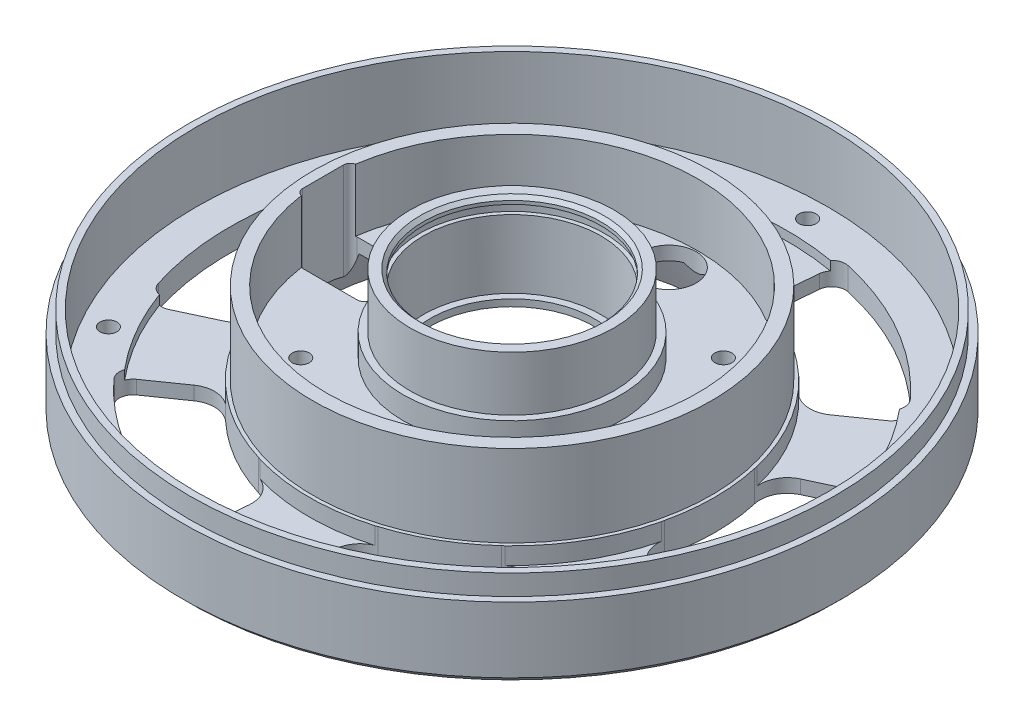
SolidWorks part; units mm, degrees
material "5052-H32"
ref_plane "Front Plane" through (0, 0, 0) normal (0, 0, 1) x (1, 0, 0)
ref_plane "Top Plane" through (0, 0, 0) normal (0, 1, 0) x (1, 0, 0)
ref_plane "Right Plane" through (0, 0, 0) normal (1, 0, 0) x (0, 0, -1)
ref_axis "Axis1" through (0, 0, 0) along (0, 1, 0)
sketch "Sketch1" plane through (0, 0, 0) normal (0, 0, 1) x (1, 0, 0)
  line L0 (0, 0) -> (0, -50000) construction
  line L1 (-13.02, 8.15) -> (-13.02, -4.15)
  line L2 (-13.02, -4.15) -> (-12.02, -4.15)
  line L4 (45.1, 8.15) -> (-45.1, 8.15) construction
  line L5 (-12.75, -4.15) -> (12.75, -4.15) construction
  line L7 (-13.02, 8.15) -> (-14.98, 8.15)
  line L8 (-14.98, 8.15) -> (-14.98, -3.15)
  line L9 (-14.98, -3.15) -> (-28.25, -3.15)
  line L10 (-12.02, -5.15) -> (-28.25, -5.15)
  line L12 (-28.25, -5.15) -> (-28.25, -3.15)
  line L13 (-29.25, 6) -> (-29.25, -6) construction
  line L16 (-12.02, -4.15) -> (-12.02, -5.15)
  dimension "D1" = 1
  dimension "D2" = 29.96
  dimension "D3" = 2
  dimension "D4" = 1
  dimension "D5" = 1
  dimension "D6" = 26.04
revolve "Revolve1" add sketch "Sketch1" angle 360 about L0
sketch "Sketch4" plane through (0, 0, 0) normal (0, 0, 1) x (1, 0, 0)
  line L1 (-29.75, -8.5) -> (-40.35, -8.5)
  line L2 (-46.35, -7.15) -> (-46.35, 3)
  line L3 (-46.35, 3) -> (-47.35, 3)
  line L4 (-47.35, 3) -> (-47.35, 0)
  line L5 (-47.35, 0) -> (-48.35, 0)
  line L6 (-48.35, 0) -> (-48.35, -9.6235)
  line L7 (-47.4735, -10.5) -> (-28.75, -10.5)
  line L8 (-28.75, -10.5) -> (-26.75, -5.15)
  line L9 (-29.75, -8.5) -> (-29.75, -6)
  line L10 (-26.75, -5.15) -> (-26.75, -3.15)
  line L12 (-48.35, -9.6235) -> (-47.4735, -10.5)
  line L13 (-45.1, 8.15) -> (-45.1, -6.15) construction
  line L14 (-46.35, -7.15) -> (-40.35, -7.15)
  line L15 (-40.35, -7.15) -> (-40.35, -8.5)
  line L16 (-45.1, -6.15) -> (45.1, -6.15) construction
  line L18 (-44.85, -7.15) -> (-44.85, -10.5) construction
  line L20 (-41.85, -7.15) -> (-41.85, -10.5) construction
  line L21 (-30.25, -6) -> (30.25, -6) construction
  line L22 (-29.75, -6) -> (-29.23, -6)
  line L23 (-29.25, -6) -> (29.25, -6) construction
  line L24 (-29.23, -6) -> (-29.23, -3.15)
  line L25 (-29.23, -3.15) -> (-26.75, -3.15)
  line L26 (28.25, -3.15) -> (-28.25, -3.15) construction
  line L27 (-39.5, -7.5) -> (39.5, -7.5) construction
  line L28 (0, 0) -> (0, 50000) construction
  line L29 (-30.25, -6) -> (-30.25, -7.5) construction
  line L33 (-28.25, -5.15) -> (28.25, -5.15) construction
  dimension "D1" = 2
  dimension "D2" = 3
  dimension "D3" = 1
  dimension "D4" = 2
  dimension "D5" = 0.5
  dimension "D6" = 1
  dimension "D7" = 1.25
  dimension "D8" = 135
  dimension "D9" = 3
  dimension "D10" = 1.5
  dimension "D11" = 1.5
  dimension "D12" = 2
  dimension "D13" = 1
  dimension "D14" = 58.46
revolve "Revolve2" add sketch "Sketch4" angle 360 about axis through (0, 0, 0) along (0, 1, 0)
sketch "Sketch6" plane through (0, 0, 0) normal (0, 0, 1) x (1, 0, 0)
  line L0 (-29.23, 6) -> (-27.23, 6)
  line L1 (-27.23, 6) -> (-27.23, -3.15)
  line L2 (-27.23, -3.15) -> (-29.23, -3.15)
  line L3 (-29.23, -3.15) -> (-29.23, 6)
  line L4 (29.25, 6) -> (-29.25, 6) construction
  line L6 (29.23, -3.15) -> (-29.23, -3.15) construction
  dimension "D1" = 2
revolve "Revolve3" add sketch "Sketch6" angle 360 about axis through (0, 0, 0) along (0, 1, 0)
sketch "Sketch7" plane through (0, 0, 0) normal (0, 0, 1) x (1, 0, 0)
  line L0 (40.35, -8.5) -> (-40.35, -8.5) construction
  line L1 (-29.58, -6) -> (-29.23, -6)
  line L2 (-29.73, -6.15) -> (-29.73, -8.5)
  line L3 (-29.73, -8.5) -> (-29.23, -8.5)
  line L4 (-29.23, -6) -> (-29.23, -8.5)
  line L5 (-29.23, 6) -> (-29.23, -6) construction
  line L6 (-29.58, -6) -> (-29.73, -6.15)
  line L7 (29.75, -8.5) -> (-29.75, -8.5) construction
  line L8 (-31.759, -6.15) -> (-25.7399, -6.15) construction
  line L13 (-30.25, -6) -> (30.25, -6) construction
  dimension "D1" = 135
  dimension "D2" = 0.5
revolve "Revolve4" add sketch "Sketch7" angle 360 about axis through (0, 0, 0) along (0, 1, 0)
sketch "Sketch8" plane through (0, -5.15, 0) normal (0, -1, 0) x (1, 0, 0)
  circle A0 centre (-15.5, 15.5) radius 3.5
  circle A1 centre (15.5, 15.5) radius 3.5
  circle A2 centre (15.5, -15.5) radius 3.5
  circle A3 centre (-15.5, -15.5) radius 3.5
  dimension "D1" = 7
sketch "Sketch10" plane through (0, 0, 0) normal (0, 0, 1) x (1, 0, 0)
  line L0 (-15.25, 0.15) -> (15.25, 0.15) construction
  line L1 (-14.98, -3.15) -> (-15.98, -3.15)
  line L2 (-14.98, -3.15) -> (-14.98, 0.15)
  line L3 (-14.98, 0.15) -> (-15.98, 0.15)
  line L4 (-15.98, -3.15) -> (-15.98, 0.15)
  line L5 (-14.98, 8.15) -> (-14.98, -3.15) construction
  line L6 (14.98, -3.15) -> (-14.98, -3.15) construction
  dimension "D1" = 1
revolve "Revolve5" add sketch "Sketch10" angle 360 about axis through (0, 0, 0) along (0, 1, 0)
sketch "Sketch12" plane through (0, 0, 0) normal (0, 1, 0) x (1, 0, 0)
  circle A0 centre (-23, 0) radius 4
  dimension "D1" = 8
  dimension "D2" = 23
extrude "Cut-Extrude2" cut sketch "Sketch12" against normal through all
pattern_circular "CirPattern3" count 4 over 360 about axis through (0, 0, 0) along (0, 1, 0) of "Cut-Extrude2"
extrude "Boss-Extrude1" add sketch "Sketch8" along normal up to surface (3.85 mm away)
hole_wizard "M3x0.5 Tapped Hole1" positions "Sketch14" profile "Sketch15" tap size "M3x0.5" standard "ANSI Metric" end condition through all
sketch "Sketch14" plane through (0, -9, 0) normal (0, -1, 0) x (-1, 0, 0)
  point P0 (-15.5, 15.5)
  point P3 (15.5, 15.5)
  point P6 (15.5, -15.5)
  point P9 (-15.5, -15.5)
cosmetic thread "Hole Thread1" parameters "D2"=3
cosmetic thread "Hole Thread2" parameters "D2"=3
cosmetic thread "Hole Thread3" parameters "D2"=3
cosmetic thread "Hole Thread4" parameters "D2"=3
sketch "Sketch15" plane through (15.5, -9, -15.5) normal (1, 0, 0) x (0, 0, -1)
  line L0 (0, 0) -> (0, 17.15)
  line L1 (0, 17.15) -> (1.25, 17.15)
  line L2 (1.25, 17.15) -> (1.25, 0)
  line L5 (1.25, 0) -> (0, 0)
  line L11 (0, -6.35) -> (0, 107.95) construction
  dimension "Thru Tap Drill Dia." = 2.5
  dimension "Thru Tap Drill Depth" = 17.15
hole_wizard "M3x0.5 Tapped Hole3" positions "Sketch19" profile "Sketch20" tap size "M3x0.5" standard "ANSI Metric" end condition through all
sketch "Sketch19" plane through (0, -10.5, 0) normal (0, -1, 0) x (-1, 0, 0)
  line L0 (0, 0) -> (0, 43.35) construction
  line L3 (0, 0) -> (-50000, 0) construction
  circle A1 centre (0, 0) radius 43.35 construction
  circle A2 centre (0, 0) radius 40.35 construction
  point P0 (0, 43.35)
  dimension "D1" = 3
  dimension "D2" = 90
sketch "Sketch20" plane through (0, -10.5, -43.35) normal (1, 0, 0) x (0, 0, -1)
  line L0 (0, 0) -> (0, 18.65)
  line L1 (0, 18.65) -> (1.25, 18.65)
  line L2 (1.25, 18.65) -> (1.25, 0.5)
  line L3 (1.25, 0.5) -> (1.75, 0)
  line L5 (1.75, 0) -> (0, 0)
  line L6 (-1.25, 0.5) -> (-1.75, 0) construction
  line L11 (0, -6.35) -> (0, 107.95) construction
  dimension "Thru Tap Drill Dia." = 2.5
  dimension "Thru Tap Drill Depth" = 18.65
  dimension "Near C'Sink Dia." = 3.5
  dimension "Near C'Sink Angle" = 90
cosmetic thread "Hole Thread7" parameters "D2"=3
pattern_circular "CirPattern4" count 6 over 360 about axis through (0, 0, 0) along (0, 1, 0) of "M3x0.5 Tapped Hole3"
sketch "Sketch24" plane through (0, -10.5, 0) normal (0, -1, 0) x (1, 0, 0)
  line L9 (-25.6489, 5.5) -> (-44.2117, 5.5)
  line L10 (-25.6489, 5.5) -> (-25.6489, -5.5)
  line L11 (-25.6489, -5.5) -> (-44.2117, -5.5)
  line L12 (-46.2117, 3.5) -> (-46.2117, -3.5)
  arc A5 (-44.2117, -5.5) -> (-46.2117, -3.5) centre (-44.2117, -3.5) cw
  arc A6 (-44.2117, 5.5) -> (-46.2117, 3.5) centre (-44.2117, 3.5) ccw
  circle A7 centre (0, 0) radius 46.35 construction
  point P5 (-25.6489, 0)
  dimension "D2" = 2
  dimension "D1" = 11
extrude "Cut-Extrude6" [suppressed] cut sketch "Sketch24" against normal up to surface (1.5 mm away)
sketch "Sketch25" plane through (0, -10.5, 0) normal (0, -1, 0) x (1, 0, 0)
  line L5 (-25.6489, 5.5) -> (-44.2117, 5.5) construction
  line L9 (-34.6807, 5.5) -> (-44.2117, 5.5)
  line L10 (-34.6807, 5.5) -> (-34.6807, -5.5)
  line L11 (-34.6807, -5.5) -> (-44.2117, -5.5)
  line L12 (-46.2117, 3.5) -> (-46.2117, -3.5)
  line L13 (-25.6489, -5.5) -> (-44.2117, -5.5) construction
  line L14 (-46.2117, 3.5) -> (-46.2117, -3.5) construction
  arc A3 (-44.2117, -5.5) -> (-46.2117, -3.5) centre (-44.2117, -3.5) cw
  arc A4 (-44.2117, 5.5) -> (-46.2117, 3.5) centre (-44.2117, 3.5) ccw
  point P12 (-46.2117, -5.5)
  dimension "D1" = 2
extrude "Cut-Extrude7" [suppressed] cut sketch "Sketch25" against normal through all
sketch "Sketch26" plane through (0, 0, 0) normal (0, 1, 0) x (1, 0, 0)
  line L0 (0, 0) -> (-50000, 0) construction
  line L1 (31.1951, 11.1252) -> (36.6728, 13.6795)
  line L2 (31.1951, -11.1252) -> (36.6728, -13.6795)
  arc A0 (39.4249, 12.47) -> (39.4249, -12.47) centre (0, 0) cw
  arc A1 (28.9857, 6.6106) -> (28.9857, -6.6106) centre (0, 0) cw
  arc A2 (28.9857, -6.6106) -> (31.1951, -11.1252) centre (32.8856, -7.5) ccw
  arc A3 (28.9857, 6.6106) -> (31.1951, 11.1252) centre (32.8856, 7.5) cw
  circle A4 centre (0, 0) radius 46.35 construction
  arc A6 (39.4249, -12.47) -> (36.6728, -13.6795) centre (37.518, -11.8669) cw
  arc A7 (39.4249, 12.47) -> (36.6728, 13.6795) centre (37.518, 11.8669) ccw
  circle A8 centre (0, 0) radius 29.23 construction
  point P12 (28.108, -9.6857)
  point P15 (28.108, 9.6857)
  point P20 (38.6807, -14.6158)
  point P26 (38.6807, 14.6158)
  dimension "D1" = 4
  dimension "D2" = 0.5
  dimension "D4" = 2
  dimension "D6" = 5
  dimension "D3" = 50
  dimension "D5" = 15
extrude "Cut-Extrude8" cut sketch "Sketch26" against normal through all both and the other way through all
pattern_circular "CirPattern5" count 6 over 360 about axis through (0, 0, 0) along (0, 1, 0) of "Cut-Extrude8"
sketch "Sketch30" plane through (0, -10.5, 0) normal (0, -1, 0) x (1, 0, 0)
  line L1 (6.6135, 5) -> (34.3769, 5)
  line L2 (6.6135, 5) -> (6.6135, -5)
  line L3 (6.6135, -5) -> (34.3769, -5)
  line L4 (34.3769, 5) -> (34.3769, -5)
  point P4 (6.6135, 0)
  dimension "D1" = 10
extrude "Cut-Extrude13" [suppressed] cut sketch "Sketch30" against normal up to surface (5.35 mm away)
sketch "Sketch31" plane through (0, 0, 0) normal (0, 0, 1) x (1, 0, 0)
  line L0 (0, 0) -> (0, -50000) construction
  line L1 (13.02, 8.15) -> (-13.02, 8.15) construction
  line L2 (-5.4339, 7.15) -> (-13.6, 7.15)
  line L3 (-5.4339, 7.15) -> (-5.4339, 5.85)
  line L4 (-5.4339, 5.85) -> (-13.6, 5.85)
  line L5 (-13.6, 7.15) -> (-13.6, 5.85)
  dimension "D1" = 1.3
  dimension "D2" = 1
  dimension "D3" = 27.2
revolve "Cut-Revolve1" cut sketch "Sketch31" angle 360 about L0
chamfer "Chamfer1" distance 0.5 angle 45 1 edges at (0, 8.15, 13.02)
sketch "Sketch32" plane through (0, 0, 0) normal (0, 1, 0) x (1, 0, 0)
  line L1 (-18.73, 4) -> (-26.73, 4)
  line L2 (-17.73, 3) -> (-17.73, -3)
  line L3 (-18.73, -4) -> (-26.73, -4)
  line L4 (-27.73, 3) -> (-27.73, -3)
  arc A0 (-26.73, 4) -> (-27.73, 3) centre (-26.73, 3) ccw
  arc A1 (-17.73, -3) -> (-18.73, -4) centre (-18.73, -3) cw
  arc A2 (-26.73, -4) -> (-27.73, -3) centre (-26.73, -3) cw
  arc A3 (-18.73, 4) -> (-17.73, 3) centre (-18.73, 3) cw
  circle A4 centre (0, 0) radius 27.23 construction
  circle A5 centre (0, 0) radius 27.23 construction
  point P4 (-17.73, 0)
  point P16 (-27.23, 0)
  dimension "D2" = 1
  dimension "D3" = 0.5
  dimension "D1" = 8
  dimension "D4" = 10
extrude "Cut-Extrude14" cut sketch "Sketch32" against normal through all both and the other way through all
